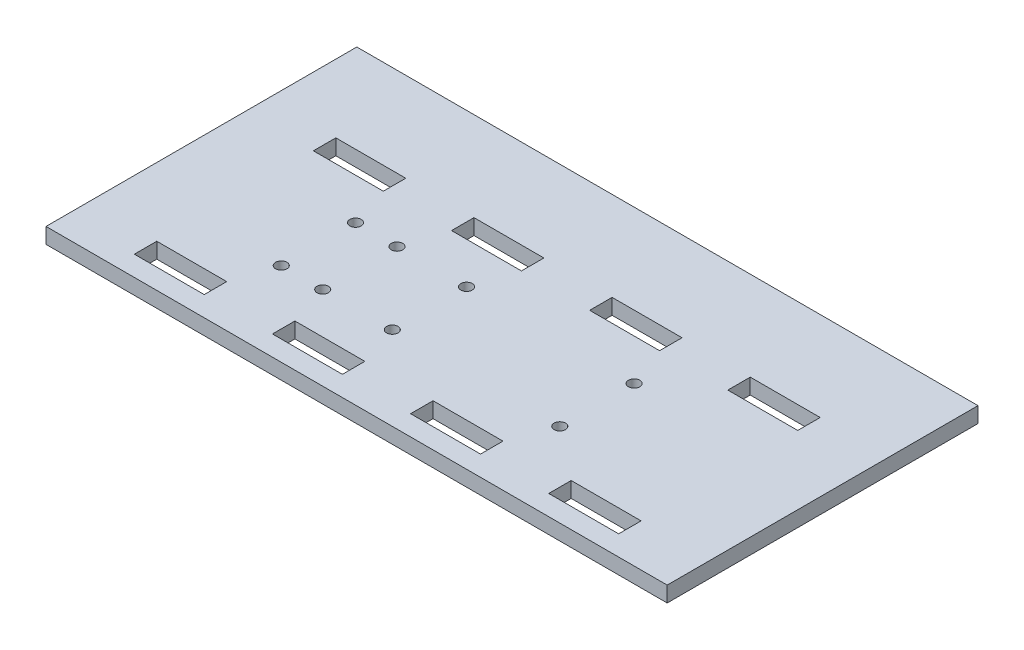
SolidWorks part; units mm, degrees
ref_plane "Front Plane" through (0, 0, 0) normal (0, 0, 1) x (1, 0, 0)
ref_plane "Top Plane" through (0, 0, 0) normal (0, 1, 0) x (1, 0, 0)
ref_plane "Right Plane" through (0, 0, 0) normal (1, 0, 0) x (0, 0, -1)
sketch "Sketch2" plane through (0, 0, 0) normal (0, 1, 0) x (1, 0, 0)
  line L3 (110, 45) -> (-110, 45)
  line L4 (110, 45) -> (110, -45)
  line L5 (110, -45) -> (-110, -45)
  line L6 (-110, 45) -> (-110, -45)
  line L7 (110, 45) -> (-110, -45) construction
  line L8 (110, -45) -> (-110, 45) construction
  point P0 (0, 0)
  dimension "D1" = 220
  dimension "D2" = 90
extrude "Boss-Extrude1" add sketch "Sketch2" along normal blind 4.5
sketch "Sketch3" plane through (0, 0, 0) normal (0, -1, 0) x (1, 0, 0)
  line L0 (0, 0) -> (0, -15.925) construction
  line L1 (50.125, -12.675) -> (50.125, -19.175)
  line L2 (10.125, -12.675) -> (-10.125, -12.675)
  line L3 (10.125, -12.675) -> (10.125, -19.175)
  line L4 (10.125, -19.175) -> (-10.125, -19.175)
  line L5 (-10.125, -12.675) -> (-10.125, -19.175)
  line L6 (10.125, -12.675) -> (-10.125, -19.175) construction
  line L7 (10.125, -19.175) -> (-10.125, -12.675) construction
  line L8 (50.125, -12.675) -> (29.875, -12.675)
  line L9 (29.875, -12.675) -> (29.875, -19.175)
  line L10 (50.125, -19.175) -> (29.875, -19.175)
  line L11 (90.125, -12.675) -> (90.125, -19.175)
  line L12 (90.125, -12.675) -> (69.875, -12.675)
  line L13 (69.875, -12.675) -> (69.875, -19.175)
  line L14 (90.125, -19.175) -> (69.875, -19.175)
  line L15 (10.125, -12.675) -> (50.125, -12.675) construction
  line L16 (-90.125, -19.175) -> (-69.875, -19.175)
  line L17 (-69.875, -12.675) -> (-69.875, -19.175)
  line L18 (-90.125, -12.675) -> (-69.875, -12.675)
  line L19 (-90.125, -12.675) -> (-90.125, -19.175)
  line L20 (-50.125, -19.175) -> (-29.875, -19.175)
  line L21 (-29.875, -12.675) -> (-29.875, -19.175)
  line L22 (-50.125, -12.675) -> (-29.875, -12.675)
  line L23 (-50.125, -12.675) -> (-50.125, -19.175)
  line L24 (0, 0) -> (0, 10) construction
  line L25 (0, 10) -> (-14.7938, 10) construction
  line L26 (10.125, 32.675) -> (50.125, 32.675) construction
  line L27 (10.125, 39.175) -> (-10.125, 32.675) construction
  line L28 (10.125, 32.675) -> (-10.125, 39.175) construction
  line L29 (-50.125, 32.675) -> (-50.125, 39.175)
  line L30 (-50.125, 32.675) -> (-29.875, 32.675)
  line L31 (-29.875, 32.675) -> (-29.875, 39.175)
  line L32 (-50.125, 39.175) -> (-29.875, 39.175)
  line L33 (-90.125, 32.675) -> (-90.125, 39.175)
  line L34 (-90.125, 32.675) -> (-69.875, 32.675)
  line L35 (-69.875, 32.675) -> (-69.875, 39.175)
  line L36 (-90.125, 39.175) -> (-69.875, 39.175)
  line L37 (90.125, 39.175) -> (69.875, 39.175)
  line L38 (69.875, 32.675) -> (69.875, 39.175)
  line L39 (90.125, 32.675) -> (69.875, 32.675)
  line L40 (90.125, 32.675) -> (90.125, 39.175)
  line L41 (50.125, 39.175) -> (29.875, 39.175)
  line L42 (29.875, 32.675) -> (29.875, 39.175)
  line L43 (50.125, 32.675) -> (29.875, 32.675)
  line L44 (-10.125, 32.675) -> (-10.125, 39.175)
  line L45 (10.125, 39.175) -> (-10.125, 39.175)
  line L46 (10.125, 32.675) -> (10.125, 39.175)
  line L47 (10.125, 32.675) -> (-10.125, 32.675)
  line L48 (50.125, 32.675) -> (50.125, 39.175)
  dimension "D1" = 12.675
  dimension "D2" = 20.25
  dimension "D3" = 6.5
  dimension "D5" = 40
  dimension "D6" = 10
  dimension "D4" = 3
extrude "Cut-Extrude1" cut sketch "Sketch3" against normal through all
sketch "Sketch4" plane through (0, 0, 0) normal (0, -1, 0) x (1, 0, 0)
  line L0 (0, 5) -> (40, 5) construction
  line L1 (0, 0) -> (0, 5) construction
  line L2 (60, 12.5) -> (20, 12.5)
  line L3 (60, 12.5) -> (60, -2.5)
  line L4 (60, -2.5) -> (20, -2.5)
  line L5 (20, 12.5) -> (20, -2.5)
  line L6 (60, 12.5) -> (20, -2.5) construction
  line L7 (60, -2.5) -> (20, 12.5) construction
  dimension "D1" = 40
  dimension "D2" = 15
  dimension "D3" = 5
  dimension "D4" = 40
extrude "Input link cut" [suppressed] cut sketch "Sketch4" against normal through all
sketch "Sketch5" plane through (0, 0, 0) normal (0, -1, 0) x (1, 0, 0)
  line L0 (54.65, 37.25) -> (54.65, -17.25) construction
  line L1 (56.9, 37.25) -> (52.4, 37.25) construction
  line L2 (52.4, -17.25) -> (56.9, -17.25) construction
  line L3 (6.15, 32.75) -> (6.15, -19.175) construction
  line L4 (3.9, 32.75) -> (8.4, 32.75) construction
  line L5 (-10.125, -19.175) -> (10.125, -19.175) construction
  line L6 (-26, -17.25) -> (-26, 37.25) construction
  line L7 (-27.75, -17.25) -> (-24.25, -17.25) construction
  line L8 (-24.25, 37.25) -> (-27.75, 37.25) construction
  line L9 (-14, -17.25) -> (-14, 37.25) construction
  line L10 (-15.75, -17.25) -> (-12.25, -17.25) construction
  line L11 (-12.25, 37.25) -> (-15.75, 37.25) construction
  line L12 (-26, 20.75) -> (58.5718, 20.75) construction
  line L13 (-10, 32.75) -> (-30, 32.75) construction
  line L14 (-26, 10) -> (-62.5697, 10) construction
  circle A0 centre (-26, 20.75) radius 1.65
  circle A1 centre (-14, 20.75) radius 1.65
  circle A2 centre (6.15, 20.75) radius 1.65
  circle A3 centre (54.65, 20.75) radius 1.65
  circle A4 centre (54.65, -0.75) radius 1.65
  circle A5 centre (6.15, -0.75) radius 1.65
  circle A6 centre (-14, -0.75) radius 1.65
  circle A7 centre (-26, -0.75) radius 1.65
  dimension "D2" = 3.3
  dimension "D1" = 12
extrude "Bracket holes" cut sketch "Sketch5" against normal through all
sketch "Sketch6" plane through (0, 0, 0) normal (0, -1, 0) x (1, 0, 0)
  line L0 (-69.875, -19.175) -> (-69.875, -12.675) construction
  line L1 (-129.3037, 54.0171) -> (-69.875, 54.0171)
  line L2 (-129.3037, 54.0171) -> (-129.3037, -58.1717)
  line L3 (-129.3037, -58.1717) -> (-69.875, -58.1717)
  line L4 (-69.875, 54.0171) -> (-69.875, -58.1717)
extrude "Trim cut" cut sketch "Sketch6" against normal through all
